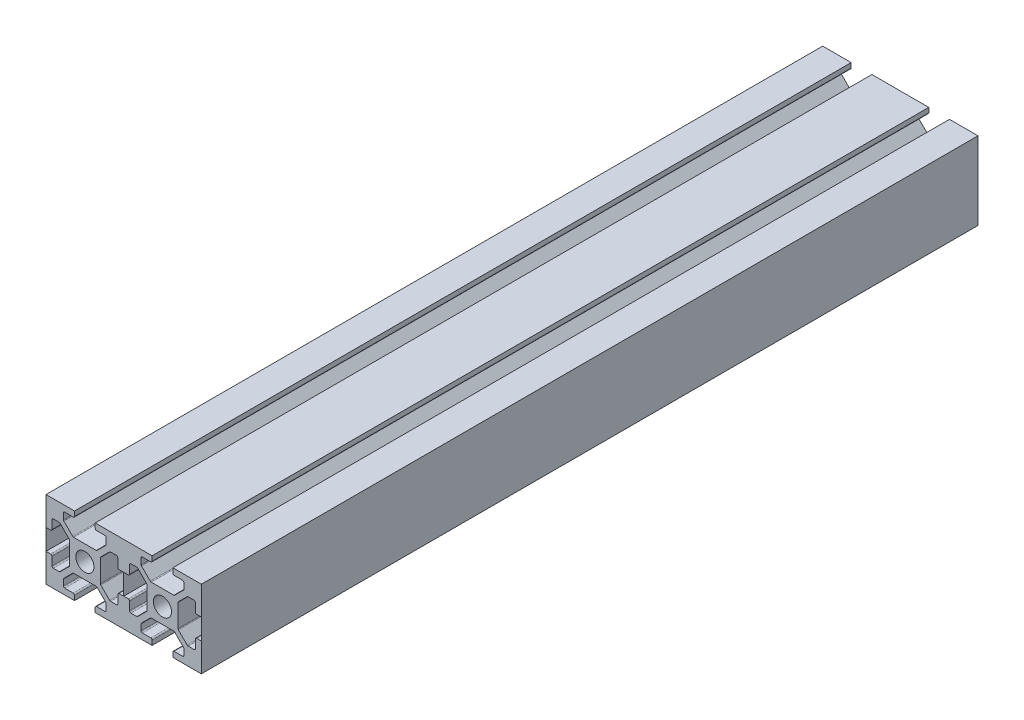
SolidWorks part; units mm, degrees
ref_plane "Alzado" through (0, 0, 0) normal (0, 0, 1) x (1, 0, 0)
ref_plane "Planta" through (0, 0, 0) normal (0, 1, 0) x (1, 0, 0)
ref_plane "Vista lateral" through (0, 0, 0) normal (1, 0, 0) x (0, 0, -1)
sketch "Croquis1" plane through (0, 0, 0) normal (0, 0, 1) x (1, 0, 0)
  line L1 (-20, -10) -> (20, -10)
  line L2 (-20, -10) -> (-20, 10)
  line L3 (-20, 10) -> (20, 10)
  line L4 (20, -10) -> (20, 10)
  line L5 (-20, -10) -> (20, 10) construction
  line L6 (-20, 10) -> (20, -10) construction
  point P0 (0, 0)
  dimension "D1" = 20
  dimension "D2" = 40
extrude "Saliente-Extruir1" add sketch "Croquis1" along normal blind 200 separate body
sketch "Croquis2" plane through (0, 0, 200) normal (0, 0, 1) x (1, 0, 0)
  line L0 (-9.99, 15) -> (-9.99, 0) construction
  line L1 (-5.99, 15) -> (-13.99, 15) construction
  line L2 (-13.99, 15) -> (-13.99, 13.2) construction
  line L3 (-14.49, 12.7) -> (-17.74, 12.7) construction
  line L4 (-18.24, 12.2) -> (-18.24, 9.9071) construction
  line L5 (-18.0936, 9.5536) -> (-14.6864, 6.1464) construction
  line L41 (-14.3329, 6) -> (-5.6471, 6) construction
  line L42 (-1.8864, 9.5536) -> (-5.2936, 6.1464) construction
  line L43 (-1.74, 12.2) -> (-1.74, 9.9071) construction
  line L44 (-5.49, 12.7) -> (-2.24, 12.7) construction
  line L45 (-5.99, 15) -> (-5.99, 13.2) construction
  line L46 (-15.3951, 6.3722) -> (-13.1225, 4.0997)
  line L47 (-6.9885, 8.4709) -> (-4.8207, 8.4709)
  line L48 (-7.322, 10.005) -> (-7.322, 8.8044)
  line L49 (-7.322, 10.005) -> (-12.658, 10.005)
  line L50 (-4.4872, 8.1374) -> (-4.4872, 6.608)
  line L51 (-9.99, 10.005) -> (-9.99, 0) construction
  line L52 (-12.9915, 8.4709) -> (-15.1593, 8.4709)
  line L53 (-4.5849, 6.3722) -> (-6.8575, 4.0997)
  line L54 (-12.658, 10.005) -> (-12.658, 8.8044)
  line L55 (-12.8867, 4.002) -> (-7.0933, 4.002)
  line L56 (-15.4928, 8.1374) -> (-15.4928, 6.608)
  line L58 (-3.6178, 5.4051) -> (-5.8903, 3.1325)
  line L59 (-5.988, 2.8967) -> (-5.988, -2.8967)
  line L60 (-3.6178, -5.4051) -> (-5.8903, -3.1325)
  line L61 (-1.8526, -5.5027) -> (-3.382, -5.5027)
  line L62 (-1.5191, -3.0015) -> (-1.5191, -5.1692)
  line L63 (0.015, -2.668) -> (-1.1856, -2.668)
  line L64 (0.015, -2.668) -> (0.015, 2.668)
  line L65 (0.015, 2.668) -> (-1.1856, 2.668)
  line L66 (-1.5191, 3.0015) -> (-1.5191, 5.1693)
  line L67 (-1.8526, 5.5028) -> (-3.382, 5.5028)
  line L68 (-4.5849, -6.3722) -> (-6.8575, -4.0997)
  line L69 (-7.0933, -4.002) -> (-12.8867, -4.002)
  line L70 (-15.3951, -6.3722) -> (-13.1225, -4.0997)
  line L71 (-15.4927, -8.1374) -> (-15.4927, -6.608)
  line L72 (-12.9915, -8.4709) -> (-15.1592, -8.4709)
  line L73 (-12.658, -10.005) -> (-12.658, -8.8044)
  line L74 (-12.658, -10.005) -> (-7.322, -10.005)
  line L75 (-7.322, -10.005) -> (-7.322, -8.8044)
  line L76 (-6.9885, -8.4709) -> (-4.8207, -8.4709)
  line L77 (-4.4872, -8.1374) -> (-4.4872, -6.608)
  line L78 (-16.3622, -5.4051) -> (-14.0897, -3.1325)
  line L79 (-13.992, -2.8967) -> (-13.992, 2.8967)
  line L80 (-16.3622, 5.4051) -> (-14.0897, 3.1325)
  line L81 (-18.1274, 5.5028) -> (-16.598, 5.5028)
  line L82 (-18.4609, 3.0015) -> (-18.4609, 5.1693)
  line L83 (-19.995, 2.668) -> (-18.7944, 2.668)
  line L84 (-19.995, 2.668) -> (-19.995, -2.668)
  line L85 (-19.995, -2.668) -> (-18.7944, -2.668)
  line L86 (-18.4609, -3.0015) -> (-18.4609, -5.1692)
  line L87 (-18.1274, -5.5027) -> (-16.598, -5.5027)
  line L88 (0, 0) -> (0, 10) construction
  line L89 (20, 10) -> (-20, 10) construction
  line L90 (4.4872, -8.1374) -> (4.4872, -6.608)
  line L91 (6.9885, -8.4709) -> (4.8207, -8.4709)
  line L92 (7.322, -10.005) -> (7.322, -8.8044)
  line L93 (12.658, -10.005) -> (7.322, -10.005)
  line L94 (12.658, -10.005) -> (12.658, -8.8044)
  line L95 (12.9915, -8.4709) -> (15.1592, -8.4709)
  line L96 (15.4927, -8.1374) -> (15.4927, -6.608)
  line L97 (15.3951, -6.3722) -> (13.1225, -4.0997)
  line L98 (7.0933, -4.002) -> (12.8867, -4.002)
  line L99 (4.5849, -6.3722) -> (6.8575, -4.0997)
  line L100 (18.1274, -5.5027) -> (16.598, -5.5027)
  line L101 (18.4609, -3.0015) -> (18.4609, -5.1692)
  line L102 (19.995, -2.668) -> (18.7944, -2.668)
  line L103 (19.995, 2.668) -> (19.995, -2.668)
  line L104 (19.995, 2.668) -> (18.7944, 2.668)
  line L105 (18.4609, 3.0015) -> (18.4609, 5.1693)
  line L106 (18.1274, 5.5028) -> (16.598, 5.5028)
  line L107 (16.3622, 5.4051) -> (14.0897, 3.1325)
  line L108 (13.992, -2.8967) -> (13.992, 2.8967)
  line L109 (16.3622, -5.4051) -> (14.0897, -3.1325)
  line L110 (1.8526, 5.5028) -> (3.382, 5.5028)
  line L111 (1.5191, 3.0015) -> (1.5191, 5.1693)
  line L112 (-0.015, 2.668) -> (1.1856, 2.668)
  line L113 (-0.015, -2.668) -> (-0.015, 2.668)
  line L114 (-0.015, -2.668) -> (1.1856, -2.668)
  line L115 (1.5191, -3.0015) -> (1.5191, -5.1692)
  line L116 (1.8526, -5.5027) -> (3.382, -5.5027)
  line L117 (3.6178, -5.4051) -> (5.8903, -3.1325)
  line L118 (5.988, 2.8967) -> (5.988, -2.8967)
  line L119 (3.6178, 5.4051) -> (5.8903, 3.1325)
  line L120 (15.4928, 8.1374) -> (15.4928, 6.608)
  line L121 (12.9915, 8.4709) -> (15.1593, 8.4709)
  line L122 (12.658, 10.005) -> (12.658, 8.8044)
  line L123 (7.322, 10.005) -> (12.658, 10.005)
  line L124 (7.322, 10.005) -> (7.322, 8.8044)
  line L125 (6.9885, 8.4709) -> (4.8208, 8.4709)
  line L126 (4.4873, 8.1374) -> (4.4873, 6.608)
  line L127 (4.5849, 6.3722) -> (6.8575, 4.0997)
  line L128 (12.8867, 4.002) -> (7.0933, 4.002)
  line L129 (15.3951, 6.3722) -> (13.1225, 4.0997)
  arc A4 (-14.6864, 6.1464) -> (-14.3329, 6) centre (-14.3329, 6.5) ccw construction
  arc A5 (-18.24, 9.9071) -> (-18.0936, 9.5536) centre (-17.74, 9.9071) ccw construction
  arc A6 (-17.74, 12.7) -> (-18.24, 12.2) centre (-17.74, 12.2) ccw construction
  arc A7 (-13.99, 13.2) -> (-14.49, 12.7) centre (-14.49, 13.2) cw construction
  circle A32 centre (-9.99, 0) radius 3.5 construction
  arc A33 (-5.99, 13.2) -> (-5.49, 12.7) centre (-5.49, 13.2) ccw construction
  arc A34 (-2.24, 12.7) -> (-1.74, 12.2) centre (-2.24, 12.2) cw construction
  arc A35 (-1.74, 9.9071) -> (-1.8864, 9.5536) centre (-2.24, 9.9071) cw construction
  arc A36 (-5.2936, 6.1464) -> (-5.6471, 6) centre (-5.6471, 6.5) cw construction
  arc A37 (-7.322, 8.8044) -> (-6.9885, 8.4709) centre (-6.9885, 8.8044) ccw
  arc A38 (-6.8575, 4.0997) -> (-7.0933, 4.002) centre (-7.0933, 4.3355) cw
  arc A39 (-15.1593, 8.4709) -> (-15.4928, 8.1374) centre (-15.1593, 8.1374) ccw
  arc A40 (-13.1225, 4.0997) -> (-12.8867, 4.002) centre (-12.8867, 4.3355) ccw
  arc A41 (-15.4928, 6.608) -> (-15.3951, 6.3722) centre (-15.1593, 6.608) ccw
  circle A42 centre (-9.99, 0) radius 2.3345
  arc A43 (-12.658, 8.8044) -> (-12.9915, 8.4709) centre (-12.9915, 8.8044) cw
  arc A44 (-4.8207, 8.4709) -> (-4.4872, 8.1374) centre (-4.8207, 8.1374) cw
  arc A45 (-4.4872, 6.608) -> (-4.5849, 6.3722) centre (-4.8207, 6.608) cw
  arc A46 (-5.8903, 3.1325) -> (-5.988, 2.8967) centre (-5.6545, 2.8967) ccw
  arc A47 (-5.8903, -3.1325) -> (-5.988, -2.8967) centre (-5.6545, -2.8967) cw
  arc A48 (-3.382, -5.5027) -> (-3.6178, -5.4051) centre (-3.382, -5.1692) cw
  arc A49 (-1.5191, -5.1692) -> (-1.8526, -5.5027) centre (-1.8526, -5.1692) cw
  arc A50 (-1.1856, -2.668) -> (-1.5191, -3.0015) centre (-1.1856, -3.0015) ccw
  arc A51 (-1.1856, 2.668) -> (-1.5191, 3.0015) centre (-1.1856, 3.0015) cw
  arc A52 (-1.5191, 5.1693) -> (-1.8526, 5.5028) centre (-1.8526, 5.1693) ccw
  arc A53 (-3.382, 5.5028) -> (-3.6178, 5.4051) centre (-3.382, 5.1693) ccw
  arc A54 (-6.8575, -4.0997) -> (-7.0933, -4.002) centre (-7.0933, -4.3355) ccw
  arc A55 (-13.1225, -4.0997) -> (-12.8867, -4.002) centre (-12.8867, -4.3355) cw
  arc A56 (-15.4927, -6.608) -> (-15.3951, -6.3722) centre (-15.1592, -6.608) cw
  arc A57 (-15.1592, -8.4709) -> (-15.4927, -8.1374) centre (-15.1592, -8.1374) cw
  arc A58 (-12.658, -8.8044) -> (-12.9915, -8.4709) centre (-12.9915, -8.8044) ccw
  arc A59 (-7.322, -8.8044) -> (-6.9885, -8.4709) centre (-6.9885, -8.8044) cw
  arc A60 (-4.8207, -8.4709) -> (-4.4872, -8.1374) centre (-4.8207, -8.1374) ccw
  arc A61 (-4.4872, -6.608) -> (-4.5849, -6.3722) centre (-4.8207, -6.608) ccw
  arc A62 (-14.0897, -3.1325) -> (-13.992, -2.8967) centre (-14.3255, -2.8967) ccw
  arc A63 (-14.0897, 3.1325) -> (-13.992, 2.8967) centre (-14.3255, 2.8967) cw
  arc A64 (-16.598, 5.5028) -> (-16.3622, 5.4051) centre (-16.598, 5.1693) cw
  arc A65 (-18.4609, 5.1693) -> (-18.1274, 5.5028) centre (-18.1274, 5.1693) cw
  arc A66 (-18.7944, 2.668) -> (-18.4609, 3.0015) centre (-18.7944, 3.0015) ccw
  arc A67 (-18.7944, -2.668) -> (-18.4609, -3.0015) centre (-18.7944, -3.0015) cw
  arc A68 (-18.4609, -5.1692) -> (-18.1274, -5.5027) centre (-18.1274, -5.1692) ccw
  arc A69 (-16.598, -5.5027) -> (-16.3622, -5.4051) centre (-16.598, -5.1692) ccw
  circle A70 centre (9.99, 0) radius 2.3345
  arc A71 (4.4872, -6.608) -> (4.5849, -6.3722) centre (4.8207, -6.608) cw
  arc A72 (4.8207, -8.4709) -> (4.4872, -8.1374) centre (4.8207, -8.1374) cw
  arc A73 (7.322, -8.8044) -> (6.9885, -8.4709) centre (6.9885, -8.8044) ccw
  arc A74 (12.658, -8.8044) -> (12.9915, -8.4709) centre (12.9915, -8.8044) cw
  arc A75 (15.1592, -8.4709) -> (15.4927, -8.1374) centre (15.1592, -8.1374) ccw
  arc A76 (15.4927, -6.608) -> (15.3951, -6.3722) centre (15.1592, -6.608) ccw
  arc A77 (13.1225, -4.0997) -> (12.8867, -4.002) centre (12.8867, -4.3355) ccw
  arc A78 (6.8575, -4.0997) -> (7.0933, -4.002) centre (7.0933, -4.3355) cw
  arc A79 (16.598, -5.5027) -> (16.3622, -5.4051) centre (16.598, -5.1692) cw
  arc A80 (18.4609, -5.1692) -> (18.1274, -5.5027) centre (18.1274, -5.1692) cw
  arc A81 (18.7944, -2.668) -> (18.4609, -3.0015) centre (18.7944, -3.0015) ccw
  arc A82 (18.7944, 2.668) -> (18.4609, 3.0015) centre (18.7944, 3.0015) cw
  arc A83 (18.4609, 5.1693) -> (18.1274, 5.5028) centre (18.1274, 5.1693) ccw
  arc A84 (16.598, 5.5028) -> (16.3622, 5.4051) centre (16.598, 5.1693) ccw
  arc A85 (14.0897, 3.1325) -> (13.992, 2.8967) centre (14.3255, 2.8967) ccw
  arc A86 (14.0897, -3.1325) -> (13.992, -2.8967) centre (14.3255, -2.8967) cw
  arc A87 (3.382, 5.5028) -> (3.6178, 5.4051) centre (3.382, 5.1693) cw
  arc A88 (1.5191, 5.1693) -> (1.8526, 5.5028) centre (1.8526, 5.1693) cw
  arc A89 (1.1856, 2.668) -> (1.5191, 3.0015) centre (1.1856, 3.0015) ccw
  arc A90 (1.1856, -2.668) -> (1.5191, -3.0015) centre (1.1856, -3.0015) cw
  arc A91 (1.5191, -5.1692) -> (1.8526, -5.5027) centre (1.8526, -5.1692) ccw
  arc A92 (3.382, -5.5027) -> (3.6178, -5.4051) centre (3.382, -5.1692) ccw
  arc A93 (5.8903, -3.1325) -> (5.988, -2.8967) centre (5.6545, -2.8967) ccw
  arc A94 (5.8903, 3.1325) -> (5.988, 2.8967) centre (5.6545, 2.8967) cw
  arc A95 (15.4928, 6.608) -> (15.3951, 6.3722) centre (15.1593, 6.608) cw
  arc A96 (15.1593, 8.4709) -> (15.4928, 8.1374) centre (15.1593, 8.1374) cw
  arc A97 (12.658, 8.8044) -> (12.9915, 8.4709) centre (12.9915, 8.8044) ccw
  arc A98 (7.322, 8.8044) -> (6.9885, 8.4709) centre (6.9885, 8.8044) cw
  arc A99 (4.8208, 8.4709) -> (4.4873, 8.1374) centre (4.8208, 8.1374) ccw
  arc A100 (4.4873, 6.608) -> (4.5849, 6.3722) centre (4.8208, 6.608) ccw
  arc A101 (6.8575, 4.0997) -> (7.0933, 4.002) centre (7.0933, 4.3355) ccw
  arc A102 (13.1225, 4.0997) -> (12.8867, 4.002) centre (12.8867, 4.3355) cw
  point P9 (-9.99, 6)
  point P30 (-9.99, 6)
  point P40 (-9.99, 4.002)
  point P61 (-9.99, 4.002)
  point P62 (-9.99, 0)
  point P108 (-9.99, 0)
  point P146 (-9.99, 0)
  line M152 (20, 10) -> (-20, 10)
  line M154 (-20, -10) -> (20, -10)
  dimension "D5" = 4.8184
  dimension "D6" = 7
  dimension "D11" = 15
  dimension "D1" = 4
  dimension "D2" = 8.25
  dimension "D3" = 135
  dimension "D4" = 4.3429
  dimension "D7" = 3.25
  dimension "D8" = 6
  dimension "D9" = 9.99
  dimension "D10" = 4
  dimension "D12" = 2.3
extrude "Cortar-Extruir1" cut sketch "Croquis2" against normal blind 200 contours A45 L50 A44 L47 A37 L48 L54 A43 L52 A39 L56 A41 L46 A40 L55 A38 L53 M152 | L87 A69 L78 A62 L79 A63 L80 A64 L81 A65 L82 A66 L83 L84 L85 A67 L86 A68 | L77 A61 L68 A54 L69 A55 L70 A56 L71 A57 L72 A58 L73 L75 A59 L76 A60 M154 | A42 | L67 A53 L58 A46 L59 A47 L60 A48 L61 A49 L62 A50 L63 L113 L65 A51 L66 A52 | A94 L119 A87 L110 A88 L111 A89 L112 L64 L114 A90 L115 A91 L116 A92 L117 A93 L118 | A102 L129 A95 L120 A96 L121 A97 L122 L124 A98 L125 A99 L126 A100 L127 A101 L128 M152 | A70 | A86 L109 A79 L100 A80 L101 A81 L102 L103 L104 A82 L105 A83 L106 A84 L107 A85 L108 | A78 L99 A71 L90 A72 L91 A73 L92 L94 A74 L95 A75 L96 A76 L97 A77 L98 M154
